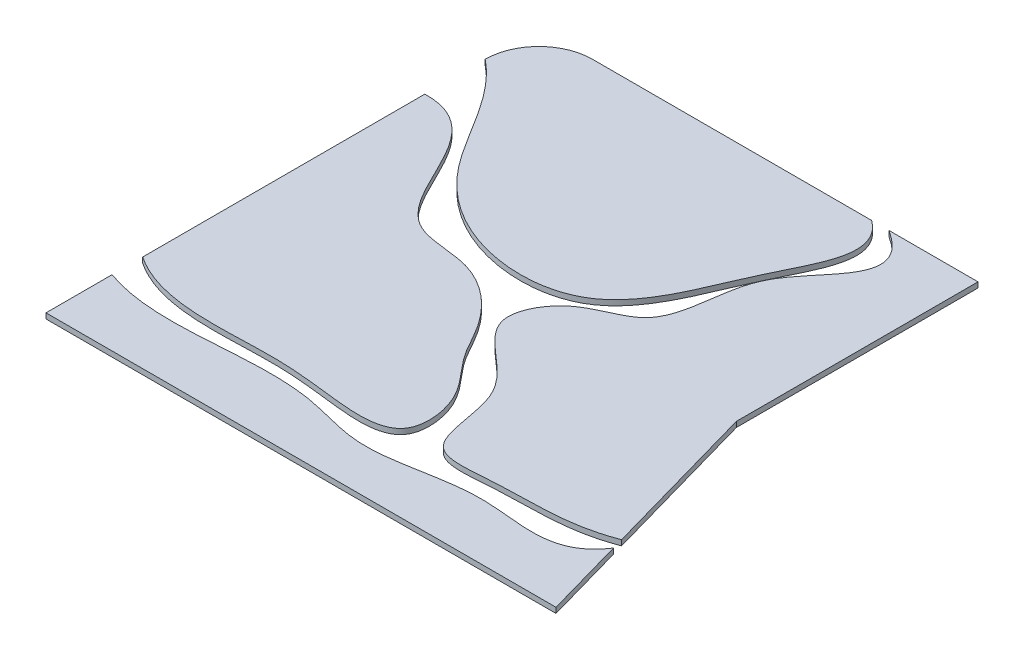
SolidWorks part; units mm, degrees
ref_plane "前视基准面" through (0, 0, 0) normal (0, 0, 1) x (1, 0, 0)
ref_plane "上视基准面" through (0, 0, 0) normal (0, 1, 0) x (1, 0, 0)
ref_plane "右视基准面" through (0, 0, 0) normal (1, 0, 0) x (0, 0, -1)
sketch "草图1" plane through (0, 0, 0) normal (0, 1, 0) x (1, 0, 0)
  line L0 (409, 458) -> (409, 8)
  line L1 (-309, 458) -> (210.8683, 458)
  line L2 (-409, 245.5804) -> (-409, -279.8829)
  line L3 (-409, -460) -> (541, -460)
  line L5 (409, 8) -> (493.03, -289.9244)
  line L8 (243, 458) -> (409, 458)
  line L9 (-409, -337) -> (-409, -460)
  line L10 (498.9237, -310.8203) -> (541, -460)
  arc A0 (-309, 458) -> (-409, 358) centre (-309, 358) ccw
  spline S0 degree 3 poles (210.8683, 458) (269.5893, 414.9308) (222.9436, 326.171) (177.7826, 228.6779) (145.1568, 147.8718) (67.2239, 35.6663) (-119.0458, 36.5042) (-246.8793, 130.6707) (-319.2215, 251.4563) (-366.459, 324.006) (-409, 358) knots 0 0 0 0 0.163728 0.235377 0.313669 0.410964 0.603028 0.75488 0.84837 1 1 1 1
  spline S1 degree 3 poles (-409, 245.5804) (-275.9931, 249.6746) (-283.6028, 7.3708) (-74.8037, 19.7447) (8.3901, -58.204) (52.9778, -153.2288) (116.99, -206.8541) (133.0006, -345.4979) (-10.0477, -329.3635) (-171.7454, -310.3636) (-318.8266, -340.3998) (-409, -279.8829) knots 0 0 0 0 0.233312 0.306255 0.417894 0.463878 0.538958 0.605999 0.700982 0.770983 1 1 1 1
  spline S2 degree 3 poles (243, 458) (349.7926, 390.9738) (213.9627, 317.055) (186.9131, 187.4466) (177.7077, 74.8563) (63.9302, 57.2136) (-6.8042, -75.317) (170.3506, -139.1916) (143.9918, -330.8659) (329.0242, -307.9153) (414.2001, -319.6888) (493.03, -289.9244) knots 0 0 0 0 0.184875 0.245348 0.332116 0.420312 0.488753 0.627086 0.74705 0.817526 1 1 1 1
  spline S3 degree 3 poles (-409, -337) (-282.0538, -381.8503) (-112.6334, -318.2548) (117.7662, -397.1101) (292.6338, -325.1902) (450.4004, -384.9514) (498.9237, -310.8203) knots 0 0 0 0 0.420682 0.530959 0.765334 1 1 1 1
  point P7 (-409, 458)
  point P12 (166.2562, -350.6628)
  point P16 (95.1939, -362.1806)
  point P20 (80.4359, -376.3078)
  point P24 (219.9989, 264.6192)
  point P32 (190.1065, 195.5237)
  point P44 (210.8683, 267.1805)
  point P52 (-253.5953, 151.5982)
  point P55 (-309, 233.4707)
  point P56 (144.8714, 154.8385)
  point P57 (179.1503, 230.194)
  point P59 (210.8683, 298.9968)
  point P61 (0, 0)
  dimension "D5" = 100
  dimension "D1" = 818
  dimension "D2" = 918
  dimension "D3" = 950
  dimension "D4" = 450
  dimension "D6" = 409
  dimension "D7" = 458
  dimension "D8" = 166
  dimension "D9" = 155
  dimension "D10" = 123
extrude "凸台-拉伸4" add sketch "草图1" along normal blind 10 contours S0 L1 A0 | L2 S1 | L0 L5 S2 L8 | L3 L10 S3 L9
